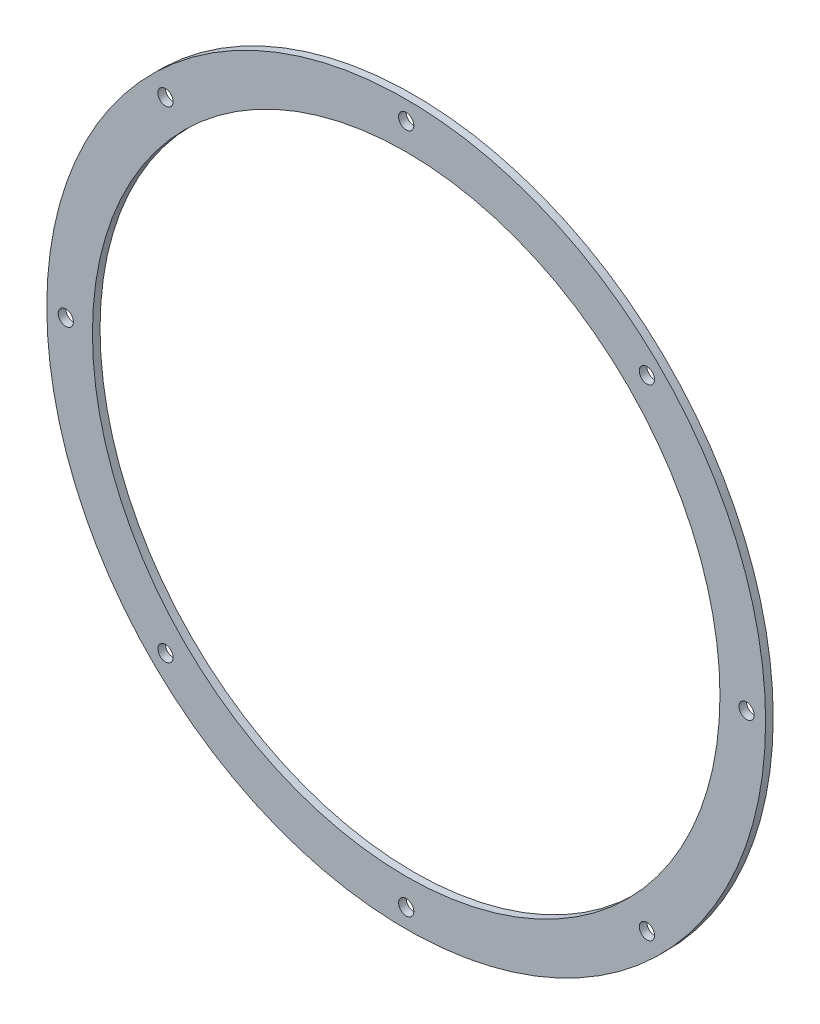
SolidWorks part; units mm, degrees
material "POLYURETHANE (11671)"
ref_plane "Front Plane" through (0, 0, 0) normal (0, 0, 1) x (1, 0, 0)
ref_plane "Top Plane" through (0, 0, 0) normal (0, 1, 0) x (1, 0, 0)
ref_plane "Right Plane" through (0, 0, 0) normal (1, 0, 0) x (0, 0, -1)
sketch "Sketch1" plane through (0, 0, 0) normal (0, 0, 1) x (1, 0, 0)
  circle A0 centre (0, 0) radius 82.5
  circle A1 centre (0, 0) radius 94.5
  circle A2 centre (0, 89.5) radius 2
  circle A3 centre (-63.2861, 63.2861) radius 2
  circle A4 centre (63.2861, 63.2861) radius 2
  circle A5 centre (89.5, 0) radius 2
  circle A6 centre (63.2861, -63.2861) radius 2
  circle A7 centre (0, -89.5) radius 2
  circle A8 centre (-63.2861, -63.2861) radius 2
  circle A9 centre (-89.5, 0) radius 2
extrude "Boss-Extrude1" add sketch "Sketch1" along normal blind 2
